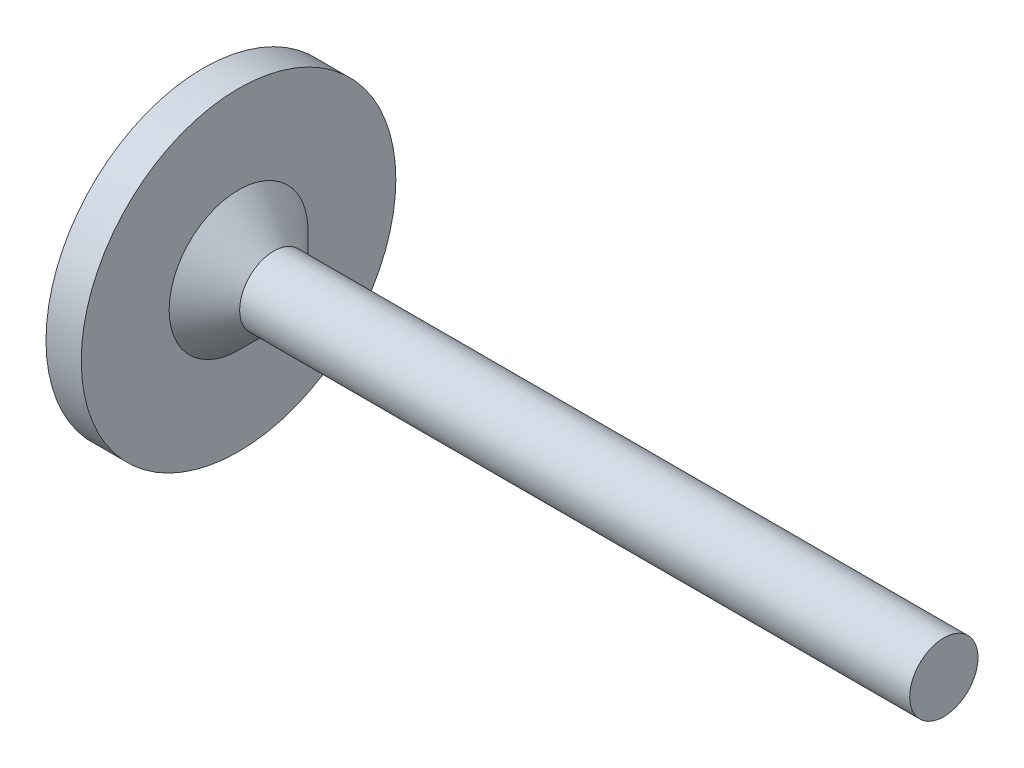
SolidWorks part; units mm, degrees
ref_plane "Front Plane" through (0, 0, 0) normal (0, 0, 1) x (1, 0, 0)
ref_plane "Top Plane" through (0, 0, 0) normal (0, 1, 0) x (1, 0, 0)
ref_plane "Right Plane" through (0, 0, 0) normal (1, 0, 0) x (0, 0, -1)
sketch "Sketch1" plane through (0, 0, 0) normal (1, 0, 0) x (0, 0, -1)
  circle A0 centre (0, 0) radius 6.15
  dimension "D1" = 12.3
extrude "Boss-Extrude1" add sketch "Sketch1" along normal blind 127
sketch "Sketch2" plane through (0, 0, 0) normal (-1, 0, 0) x (0, 0, 1)
  circle A0 centre (0, 0) radius 28.321
  dimension "D1" = 56.642
extrude "Boss-Extrude2" add sketch "Sketch2" along normal blind 6.35
chamfer "Chamfer1" distance 6.35 angle 45 1 edges at (0, 0, -6.15)
